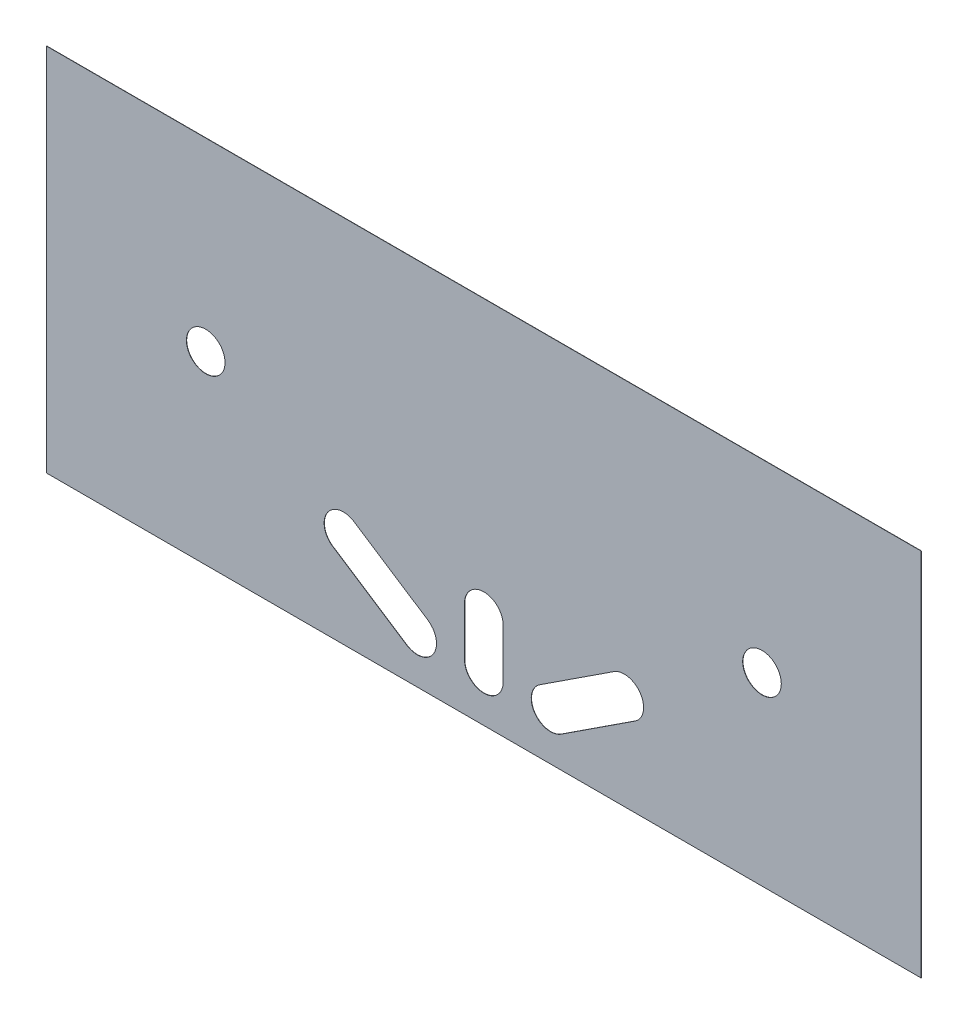
SolidWorks part; units mm, degrees
ref_plane "Front Plane" through (0, 0, 0) normal (0, 0, 1) x (1, 0, 0)
ref_plane "Top Plane" through (0, 0, 0) normal (0, 1, 0) x (1, 0, 0)
ref_plane "Right Plane" through (0, 0, 0) normal (1, 0, 0) x (0, 0, -1)
sketch "Sketch1" plane through (0, 0, 0) normal (0, 0, 1) x (1, 0, 0)
  line L1 (17, -7.1881) -> (-17, -7.1881)
  line L2 (17, -7.1881) -> (17, 7.1881)
  line L3 (17, 7.1881) -> (-17, 7.1881)
  line L4 (-17, -7.1881) -> (-17, 7.1881)
  line L5 (17, -7.1881) -> (-17, 7.1881) construction
  line L6 (17, 7.1881) -> (-17, -7.1881) construction
  arc A0 (-16.6369, 3.1864) -> (-16.7422, 2.4757) centre (-16.6369, 2.8233) ccw construction
  point P0 (0, 0)
extrude "Boss-Extrude1" add sketch "Sketch1" along normal blind 0.01
sketch "Sketch2" plane through (0, 0, 0.01) normal (0, 0, 1) x (1, 0, 0)
  line L0 (0, -5.35) -> (0, -3.4361) construction
  line L4 (5.46, -3.4751) -> (2.5913, -5.35) construction
  line L5 (5.46, -3.1501) -> (5.46, -3.8001) construction
  line L6 (5.8703, -4.1029) -> (3.0016, -5.9778)
  line L7 (5.0497, -2.8473) -> (2.181, -4.7222)
  line L8 (2.1913, -5.35) -> (2.9913, -5.35) construction
  line L9 (2.1913, -5.077) -> (2.1913, -5.6231) construction
  line L10 (2.9913, -5.6231) -> (2.9913, -5.077) construction
  line L11 (0, 0) -> (0, -9.4248) construction
  line L12 (-5.46, -3.4751) -> (-2.5913, -5.35) construction
  line L13 (-5.8703, -4.1029) -> (-3.0016, -5.9778)
  line L14 (-5.0497, -2.8473) -> (-2.181, -4.7222)
  line L15 (-0.75, -5.35) -> (-0.75, -3.4361)
  line L16 (0.75, -5.35) -> (0.75, -3.4361)
  line L17 (-0.4, -5.35) -> (0.4, -5.35) construction
  line L18 (-0.4, -5.077) -> (-0.4, -5.6231) construction
  line L19 (0.4, -5.6231) -> (0.4, -5.077) construction
  line L20 (-2.5913, -6.1) -> (2.5913, -6.1) construction
  arc A2 (5.8703, -4.1029) -> (5.0497, -2.8473) centre (5.46, -3.4751) ccw
  arc A3 (2.181, -4.7222) -> (3.0016, -5.9778) centre (2.5913, -5.35) ccw
  arc A4 (-5.8703, -4.1029) -> (-5.0497, -2.8473) centre (-5.46, -3.4751) cw
  arc A5 (-2.181, -4.7222) -> (-3.0016, -5.9778) centre (-2.5913, -5.35) cw
  arc A6 (-0.75, -5.35) -> (0.75, -5.35) centre (0, -5.35) ccw
  arc A7 (0.75, -3.4361) -> (-0.75, -3.4361) centre (0, -3.4361) ccw
  circle A8 centre (10.8135, 0) radius 0.75
  circle A10 centre (-10.8135, 0) radius 0.75
  point P2 (0, -4.393)
  point P15 (4.0257, -4.4126)
  point P28 (-4.0257, -4.4126)
  dimension "D3" = 1.5
  dimension "D1" = 1.5
  dimension "D2" = 1.5
extrude "Cut-Extrude1" cut sketch "Sketch2" against normal through all both and the other way through all
